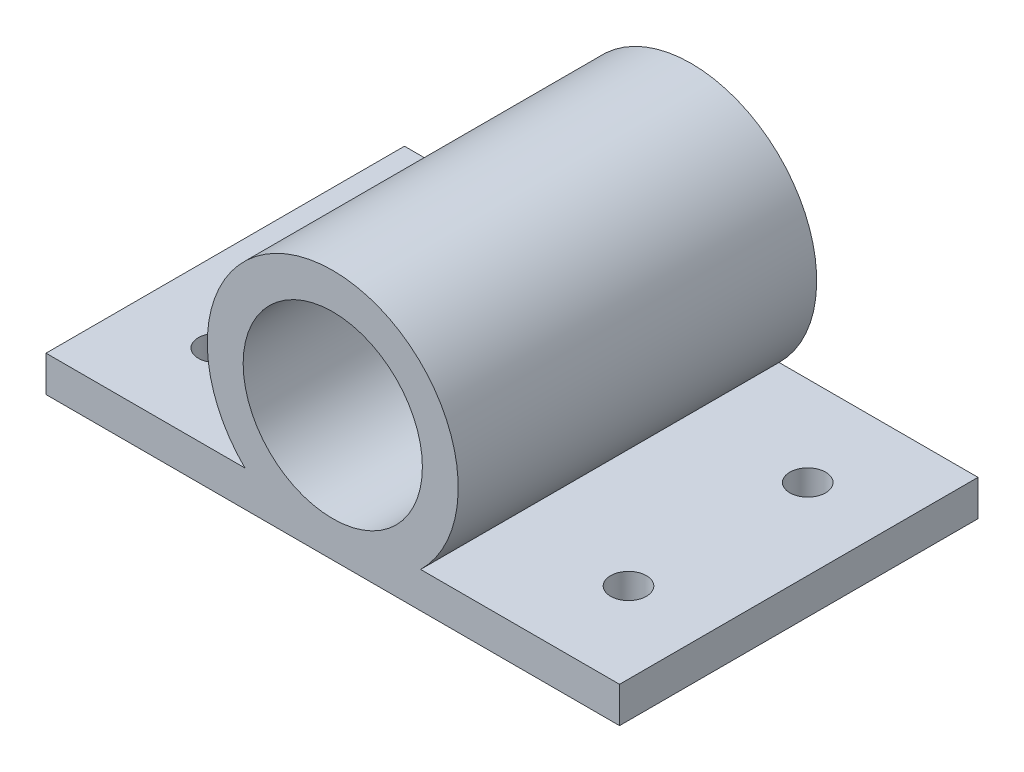
SolidWorks part; units mm, degrees
ref_plane "Front Plane" through (0, 0, 0) normal (0, 0, 1) x (1, 0, 0)
ref_plane "Top Plane" through (0, 0, 0) normal (0, 1, 0) x (1, 0, 0)
ref_plane "Right Plane" through (0, 0, 0) normal (1, 0, 0) x (0, 0, -1)
sketch "Sketch2" plane through (0, 0, 0) normal (0, 0, 1) x (1, 0, 0)
  line L0 (0, 0) -> (0, -35) construction
  line L1 (-80, -35) -> (80, -35)
  line L2 (-80, -35) -> (-80, -25)
  line L3 (-80, -25) -> (-24.4949, -25)
  line L4 (80, -35) -> (80, -25)
  line L5 (24.4949, -25) -> (80, -25)
  circle A1 centre (0, 0) radius 25
  arc A2 (-24.4949, -25) -> (24.4949, -25) centre (0, 0) cw
  point P1 (0, 0)
  point P11 (0, -35)
  dimension "D1" = 50
  dimension "D2" = 35
  dimension "D3" = 10
  dimension "D4" = 160
  dimension "D5" = 55.5051
extrude "Boss-Extrude1" add sketch "Sketch2" along normal blind 100
sketch "Sketch3" plane through (0, -25, 0) normal (0, 1, 0) x (1, 0, 0)
  line L0 (52.2474, 0) -> (52.2474, -100) construction
  line L1 (80, 0) -> (24.4949, 0) construction
  line L2 (80, -100) -> (24.4949, -100) construction
  line L3 (52.2474, -50) -> (80, -50) construction
  line L4 (80, -100) -> (80, 0) construction
  line L5 (52.2474, -50) -> (-80, -50) construction
  line L6 (-80, -100) -> (-80, 0) construction
  line L7 (-52.2474, 0) -> (-52.2474, -100) construction
  line L8 (-24.4949, 0) -> (-80, 0) construction
  line L9 (-24.4949, -100) -> (-80, -100) construction
  line L10 (-35, 0) -> (-80, -50) construction
  line L11 (-80, -50) -> (-35, -100) construction
  line L12 (-35, -100) -> (35, -100) construction
  line L13 (-35, 0) -> (-35, -100) construction
  line L14 (35, 0) -> (80, -50) construction
  line L15 (80, -50) -> (35, -100) construction
  circle A0 centre (57.5, -25) radius 5
  circle A1 centre (57.5, -75) radius 5
  circle A2 centre (-57.5, -25) radius 5
  circle A3 centre (-57.5, -75) radius 5
  dimension "D1" = 10
  dimension "D2" = 10
  dimension "D3" = 10
  dimension "D4" = 10
extrude "Cut-Extrude1" cut sketch "Sketch3" against normal blind 10
